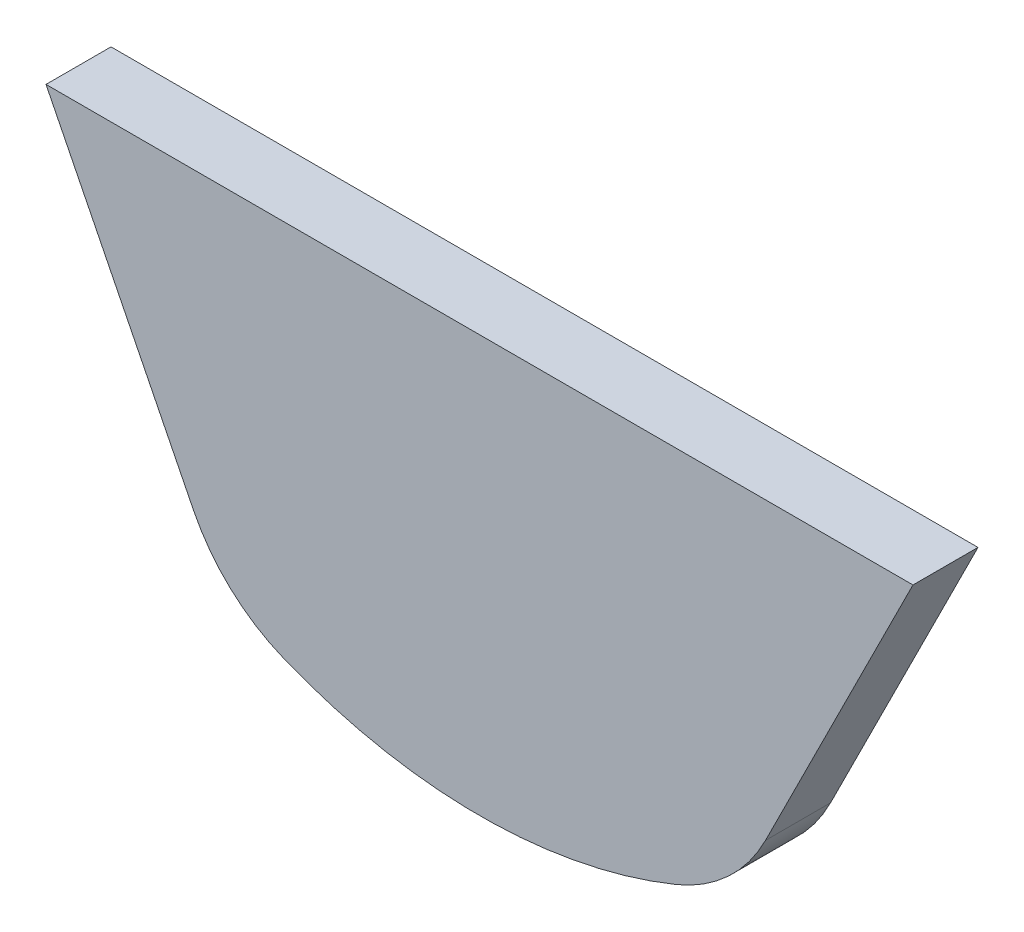
SolidWorks part; units mm, degrees
ref_plane "Front Plane" through (0, 0, 0) normal (0, 0, 1) x (1, 0, 0)
ref_plane "Top Plane" through (0, 0, 0) normal (0, 1, 0) x (1, 0, 0)
ref_plane "Right Plane" through (0, 0, 0) normal (1, 0, 0) x (0, 0, -1)
sketch "Sketch1" plane through (0, 0, 0) normal (0, 0, 1) x (1, 0, 0)
  line L0 (-127, 0) -> (127, 0)
  line L1 (0, -58.3504) -> (0, 61.0114) construction
  line L2 (-127, 0) -> (-76.2, -101.6)
  line L4 (76.2, -101.6) -> (127, 0)
  arc A0 (-76.2, -101.6) -> (76.2, -101.6) centre (0, 30.3823) ccw
  dimension "D1" = 152.4
  dimension "D2" = 254
  dimension "D3" = 101.6
  dimension "D4" = 152.4
extrude "Boss-Extrude1" add sketch "Sketch1" along normal blind 19.05
sketch "Sketch2" plane through (0, 0, 19.05) normal (0, 0, 1) x (1, 0, 0)
  line L0 (0, -25.4) -> (0, -101.6) construction
  line L1 (9.525, -25.4) -> (9.525, -101.6)
  line L2 (-9.525, -25.4) -> (-9.525, -101.6)
  line L3 (127, 0) -> (-127, 0) construction
  arc A0 (9.525, -25.4) -> (-9.525, -25.4) centre (0, -25.4) ccw
  arc A1 (-9.525, -101.6) -> (9.525, -101.6) centre (0, -101.6) ccw
  point P3 (0, -63.5)
  dimension "D3" = 25.4
  dimension "D1" = 19.05
  dimension "D2" = 76.2
extrude "Cut-Extrude1" [suppressed] cut sketch "Sketch2" against normal blind 6.35
fillet "Fillet1" radius 50.8 2 edges at (76.2, -101.6, 9.525) (-76.2, -101.6, 9.525)
